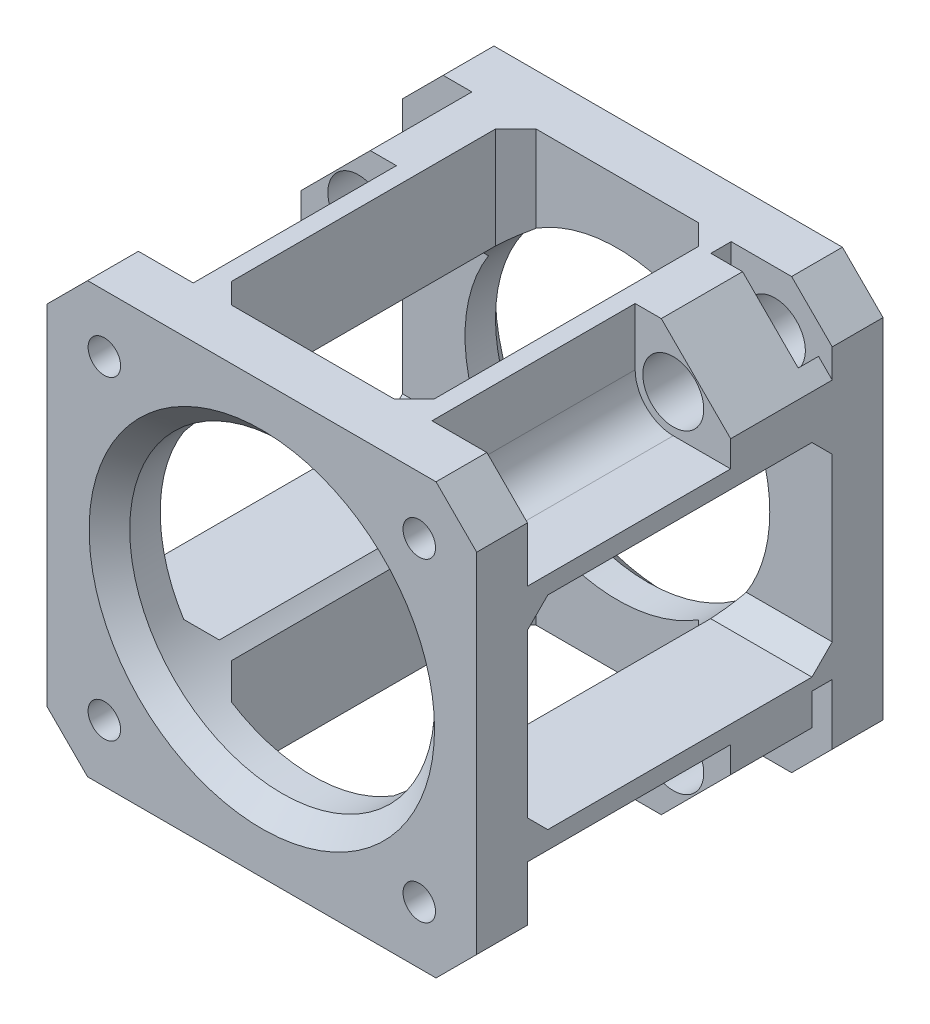
SolidWorks part; units mm, degrees
ref_plane "Front Plane" through (0, 0, 0) normal (0, 0, 1) x (1, 0, 0)
ref_plane "Top Plane" through (0, 0, 0) normal (0, 1, 0) x (1, 0, 0)
ref_plane "Right Plane" through (0, 0, 0) normal (1, 0, 0) x (0, 0, -1)
sketch "Sketch1" plane through (0, 0, 0) normal (0, 0, 1) x (1, 0, 0)
  line L1 (0, 0) -> (42.3, 0)
  line L2 (0, 0) -> (0, 42.3)
  line L3 (0, 42.3) -> (42.3, 42.3)
  line L4 (42.3, 0) -> (42.3, 42.3)
  line L5 (5.65, 36.65) -> (36.65, 36.65)
  line L6 (5.65, 36.65) -> (5.65, 5.65)
  line L7 (5.65, 5.65) -> (36.65, 5.65)
  line L8 (36.65, 36.65) -> (36.65, 5.65)
  line L9 (5.65, 36.65) -> (36.65, 5.65) construction
  line L10 (5.65, 5.65) -> (36.65, 36.65) construction
  circle A0 centre (5.65, 36.65) radius 1.6
  circle A1 centre (5.65, 5.65) radius 1.6
  circle A2 centre (36.65, 5.65) radius 1.6
  circle A3 centre (36.65, 36.65) radius 1.6
  point P5 (21.15, 21.15)
  point P20 (21.15, 21.15)
  dimension "D7" = 3.2
  dimension "D1" = 42.3
  dimension "D2" = 42.3
  dimension "D3" = 21.15
  dimension "D4" = 21.15
  dimension "D5" = 31
  dimension "D6" = 31
  dimension "D8" = 4
extrude "Boss-Extrude1" add sketch "Sketch1" along normal blind 40 contours L1 L4 L3 L2 A3 L8 A2 L7 A1 L6 A0 L5 | A3 L5 A0 L6 A1 L7 A2 L8
sketch "Sketch2" plane through (0, 0, 40) normal (0, 0, 1) x (1, 0, 0)
  circle A0 centre (21.15, 21.15) radius 15
  dimension "D1" = 30
extrude "Cut-Extrude1" cut sketch "Sketch2" against normal blind 40
chamfer "Chamfer1" distance 4 angle 45 4 edges at (42.3, 42.3, 20) (42.3, 0, 20) (0, 0, 20) (0, 42.3, 20)
chamfer "Chamfer2" distance 2 angle 45 2 edges at (36.15, 21.15, 0) (36.15, 21.15, 40)
sketch "Sketch3" plane through (42.3, 0, 0) normal (1, 0, 0) x (0, 0, -1)
  line L0 (-40, 4) -> (0, 4) construction
  line L1 (-35, 31.15) -> (-5, 31.15)
  line L2 (-35, 31.15) -> (-35, 11.15)
  line L3 (-35, 11.15) -> (-5, 11.15)
  line L4 (-5, 31.15) -> (-5, 11.15)
  line L5 (-35, 31.15) -> (-5, 11.15) construction
  line L6 (-35, 11.15) -> (-5, 31.15) construction
  line L7 (-40, 4) -> (-40, 38.3) construction
  point P0 (-20, 21.15)
  dimension "D1" = 20
  dimension "D2" = 17.15
  dimension "D3" = 20
  dimension "D4" = 30
extrude "Cut-Extrude2" cut sketch "Sketch3" against normal through all
sketch "Sketch4" plane through (0, 42.3, 0) normal (0, 1, 0) x (1, 0, 0)
  line L0 (4, -40) -> (38.3, -40) construction
  line L1 (11.15, -5) -> (31.15, -5)
  line L2 (11.15, -5) -> (11.15, -35)
  line L3 (11.15, -35) -> (31.15, -35)
  line L4 (31.15, -5) -> (31.15, -35)
  line L5 (11.15, -5) -> (31.15, -35) construction
  line L6 (11.15, -35) -> (31.15, -5) construction
  line L7 (38.3, -40) -> (38.3, 0) construction
  point P0 (21.15, -20)
  dimension "D1" = 20
  dimension "D2" = 17.15
  dimension "D3" = 20
  dimension "D4" = 30
extrude "Cut-Extrude3" cut sketch "Sketch4" against normal through all
chamfer "Chamfer3" distance 2 angle 45 16 edges at (37.3152, 31.15, 35) (37.3152, 11.15, 35) (11.15, 4.9848, 35) (31.15, 4.9848, 35) (4.9848, 31.15, 35) (4.9848, 11.15, 35) (11.15, 4.9848, 5) (31.15, 4.9848, 5) (37.3152, 11.15, 5) (37.3152, 31.15, 5) (4.9848, 31.15, 5) (4.9848, 11.15, 5) (31.15, 37.3152, 35) (31.15, 37.3152, 5) (11.15, 37.3152, 5) (11.15, 37.3152, 35)
sketch "Sketch5" plane through (-19.15, 19.15, 0) normal (-0.7071, 0.7071, 0) x (0, 0, 1)
  line L0 (40, 32.739) -> (40, 27.0822) construction
  line L1 (5, 37.4106) -> (35, 37.4106)
  line L2 (5, 37.4106) -> (5, 22.4106)
  line L3 (5, 22.4106) -> (35, 22.4106)
  line L4 (35, 37.4106) -> (35, 22.4106)
  line L5 (5, 37.4106) -> (35, 22.4106) construction
  line L6 (5, 22.4106) -> (35, 37.4106) construction
  line L7 (40, 27.0822) -> (0, 27.0822) construction
  point P0 (20, 29.9106)
  dimension "D1" = 20
  dimension "D2" = 2.8284
  dimension "D3" = 15
  dimension "D4" = 30
extrude "Cut-Extrude5" cut sketch "Sketch5" against normal blind 2
pattern_circular "CirPattern1" count 4 over 360 about axis through (21.15, 21.15, 0) along (0, 0, 1) of "Cut-Extrude5"
sketch "Sketch8" plane through (0, 0, 5) normal (0, 0, 1) x (1, 0, 0)
  line L1 (32.35, 40.95) -> (40.95, 40.95)
  line L2 (32.35, 40.95) -> (32.35, 32.35)
  line L3 (32.35, 32.35) -> (40.95, 32.35)
  line L4 (40.95, 40.95) -> (40.95, 32.35)
  line L5 (32.35, 40.95) -> (40.95, 32.35) construction
  line L6 (32.35, 32.35) -> (40.95, 40.95) construction
  line L7 (32.35, 40.95) -> (40.95, 40.95)
  line L8 (32.35, 40.95) -> (32.35, 42.3)
  line L9 (32.35, 42.3) -> (40.95, 42.3)
  line L10 (40.95, 40.95) -> (40.95, 42.3)
  point P0 (36.65, 36.65)
  line M3 (42.3, 38.3) -> (38.3, 42.3)
  line M4 (38.3, 42.3) -> (35.4716, 42.3)
  line M5 (35.4716, 42.3) -> (42.3, 35.4716)
  dimension "D1" = 8.6
  dimension "D2" = 8.6
extrude "Cut-Extrude6" cut sketch "Sketch8" along normal blind 2 contours L4 L1 L2 L3 M5 | L1 M5 M3 M4 | L9 L8 L1 M5 | L4 L1 M3 M5 | L1 L10 L9 M3
pattern_circular "CirPattern2" count 4 every 90 about axis through (21.15, 21.15, 0) along (0, 0, 1) of "Cut-Extrude6"
sketch "Sketch9" plane through (0, 0, 35) normal (0, 0, -1) x (-1, 0, 0)
  line L0 (-36.65, 32.9) -> (-42.3, 32.9)
  line L1 (-42.3, 4) -> (-42.3, 38.3) construction
  line L2 (-42.3, 32.9) -> (-42.3, 38.3)
  line L3 (-42.3, 38.3) -> (-38.3, 42.3)
  line L4 (-38.3, 42.3) -> (-32.9, 42.3)
  line L5 (-4, 42.3) -> (-38.3, 42.3) construction
  line L6 (-32.9, 42.3) -> (-32.9, 36.65)
  arc A0 (-36.65, 32.9) -> (-32.9, 36.65) centre (-36.65, 36.65) ccw
  dimension "D1" = 7.5
extrude "Cut-Extrude7" cut sketch "Sketch9" along normal blind 20 contours A0 L6 L4 L3 L2 L0
pattern_circular "CirPattern3" count 4 every 90 about axis through (21.15, 21.15, 0) along (0, 0, 1) of "Cut-Extrude7"
sketch "Sketch10" plane through (0, 0, 0) normal (0, 0, -1) x (-1, 0, 0)
  circle A0 centre (-36.65, 36.65) radius 3
  circle A1 centre (-5.65, 36.65) radius 3
  circle A2 centre (-5.65, 5.65) radius 3
  circle A3 centre (-36.65, 5.65) radius 3
  point P12 (-21.15, 21.15)
  dimension "D1" = 6
  dimension "D2" = 4
extrude "Cut-Extrude8" cut sketch "Sketch10" against normal blind 20
